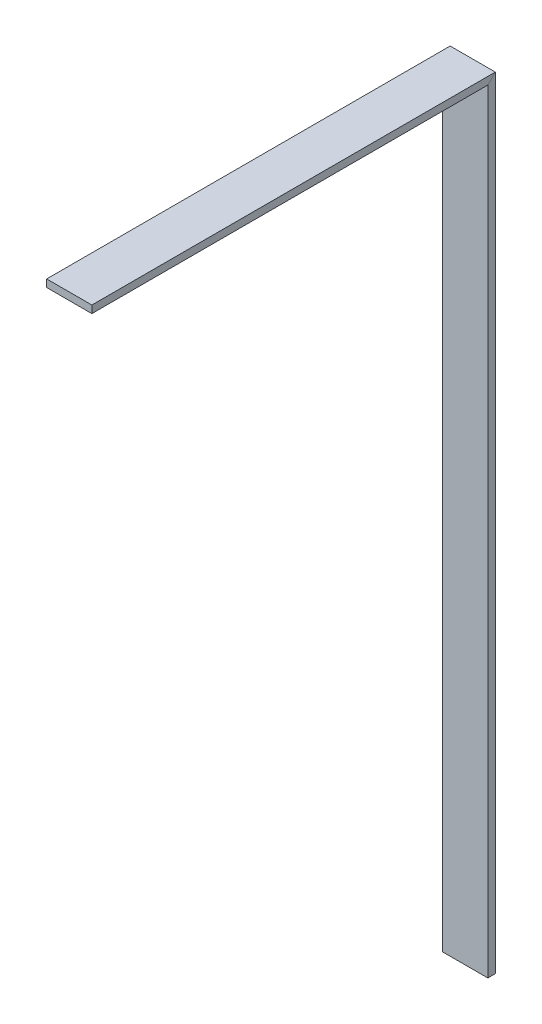
SolidWorks part; units mm, degrees
ref_plane "Alzado" through (0, 0, 0) normal (0, 0, 1) x (1, 0, 0)
ref_plane "Planta" through (0, 0, 0) normal (0, 1, 0) x (1, 0, 0)
ref_plane "Vista lateral" through (0, 0, 0) normal (1, 0, 0) x (0, 0, -1)
sketch "Croquis1" plane through (0, 0, 0) normal (0, 0, 1) x (1, 0, 0)
  line L1 (-19.05, 425.25) -> (19.05, 425.25)
  line L2 (-19.05, 425.25) -> (-19.05, -425.25)
  line L3 (-19.05, -425.25) -> (19.05, -425.25)
  line L4 (19.05, 425.25) -> (19.05, -425.25)
  line L5 (-19.05, 425.25) -> (19.05, -425.25) construction
  line L6 (-19.05, -425.25) -> (19.05, 425.25) construction
  point P0 (0, 0)
  dimension "D1" = 38.1
  dimension "D2" = 850.5
extrude "Saliente-Extruir1" add sketch "Croquis1" along normal blind 6.31
sketch "Croquis2" plane through (0, 0, 6.31) normal (0, 0, 1) x (1, 0, 0)
  line L0 (-19.05, -425.25) -> (19.05, -425.25) construction
  line L1 (-19.05, -418.94) -> (19.05, -418.94)
  line L2 (-19.05, -418.94) -> (-19.05, -425.25)
  line L3 (-19.05, -425.25) -> (19.05, -425.25)
  line L4 (19.05, -418.94) -> (19.05, -425.25)
  line L5 (-19.05, -418.94) -> (19.05, -425.25) construction
  line L6 (-19.05, -425.25) -> (19.05, -418.94) construction
  line L7 (-19.05, 425.25) -> (-19.05, -425.25) construction
  point P0 (0, -422.095)
  dimension "D1" = 6.31
extrude "Saliente-Extruir2" add sketch "Croquis2" along normal blind 70
sketch "Croquis3" plane through (0, 0, 6.31) normal (0, 0, 1) x (1, 0, 0)
  line L0 (-19.05, -425.25) -> (-19.05, -274.75) construction
  line L1 (-19.05, 425.25) -> (-19.05, -418.94) construction
  line L2 (19.05, -418.94) -> (19.05, 425.25) construction
  line L3 (-19.05, -262.4761) -> (19.05, -262.4761)
  line L4 (-19.05, -262.4761) -> (-19.05, -268.7861)
  line L5 (-19.05, -268.7861) -> (19.05, -268.7861)
  line L6 (19.05, -262.4761) -> (19.05, -268.7861)
  line L7 (-19.05, -262.4761) -> (19.05, -268.7861) construction
  line L8 (-19.05, -268.7861) -> (19.05, -262.4761) construction
  point P5 (0, -265.6311)
  dimension "D1" = 150.5
  dimension "D2" = 6.31
  dimension "D3" = 38.1
extrude "Saliente-Extruir3" add sketch "Croquis3" against normal blind 578
sketch "Croquis4" plane through (0, -262.4761, 0) normal (0, 1, 0) x (1, 0, 0)
  circle A0 centre (0, 536.9815) radius 6.9359
extrude "Cortar-Extruir1" cut sketch "Croquis4" against normal blind 7
sketch "Croquis5" plane through (0, 0, 0) normal (0, 0, -1) x (-1, 0, 0)
  line L0 (-19.05, 425.25) -> (19.05, 425.25)
  line L1 (19.05, 425.25) -> (19.05, -262.4761)
  line L2 (19.05, -262.4761) -> (-19.05, -262.4761)
  line L3 (-19.05, -262.4761) -> (-19.05, 425.25)
extrude "Cortar-Extruir2" cut sketch "Croquis5" against normal blind 10
sketch "Croquis6" plane through (0, -262.4761, 0) normal (0, 1, 0) x (1, 0, 0)
  line L0 (0, -6.31) -> (0, 196.49) construction
  line L1 (19.05, -6.31) -> (-19.05, -6.31) construction
  line L2 (19.05, 202.8) -> (-19.05, 202.8)
  line L3 (19.05, 571.69) -> (19.05, -6.31) construction
  line L4 (-19.05, 571.69) -> (-19.05, -6.31) construction
  line L5 (-19.05, 202.8) -> (-19.05, 196.49)
  line L6 (-19.05, 196.49) -> (19.05, 196.49)
  line L7 (19.05, 196.49) -> (19.05, 202.8)
  line L8 (19.05, 202.8) -> (-19.05, 196.49) construction
  line L9 (-19.05, 202.8) -> (19.05, 196.49) construction
  dimension "D1" = 202.8
  dimension "D2" = 6.31
sketch3d "Croquis3D1"
  line L0 (0, -262.4761, -199.645) -> (0, 386.8539, -199.645)
  line L1 (19.05, -262.4761, -202.8) -> (-19.05, -262.4761, -196.49) construction
  line L2 (0, 386.8539, -199.645) -> (0, 386.8539, 137.595)
  dimension "D1" = 649.33
  dimension "D2" = 337.24
sweep "Barrer1" add profiles "Croquis6" path "Croquis3D1"
sketch "Croquis8" plane through (19.05, 0, 0) normal (1, 0, 0) x (0, 0, -1)
  line L0 (196.49, -262.4761) -> (196.49, -268.7861)
  line L1 (571.69, -268.7861) -> (0, -268.7861) construction
  line L2 (196.49, -268.7861) -> (196.49, -444.3077)
  line L3 (196.49, -444.3077) -> (-90.8346, -444.3077)
  line L4 (-90.8346, -444.3077) -> (-90.8346, -262.4761)
  line L5 (-90.8346, -262.4761) -> (196.49, -262.4761)
  line L6 (202.8, -262.4761) -> (202.8, -268.7861)
  line L7 (202.8, -268.7861) -> (571.69, -268.7861)
  line L8 (571.69, -268.7861) -> (571.69, -262.4761)
  line L9 (571.69, -262.4761) -> (202.8, -262.4761)
extrude "Cortar-Extruir3" cut sketch "Croquis8" against normal blind 147
